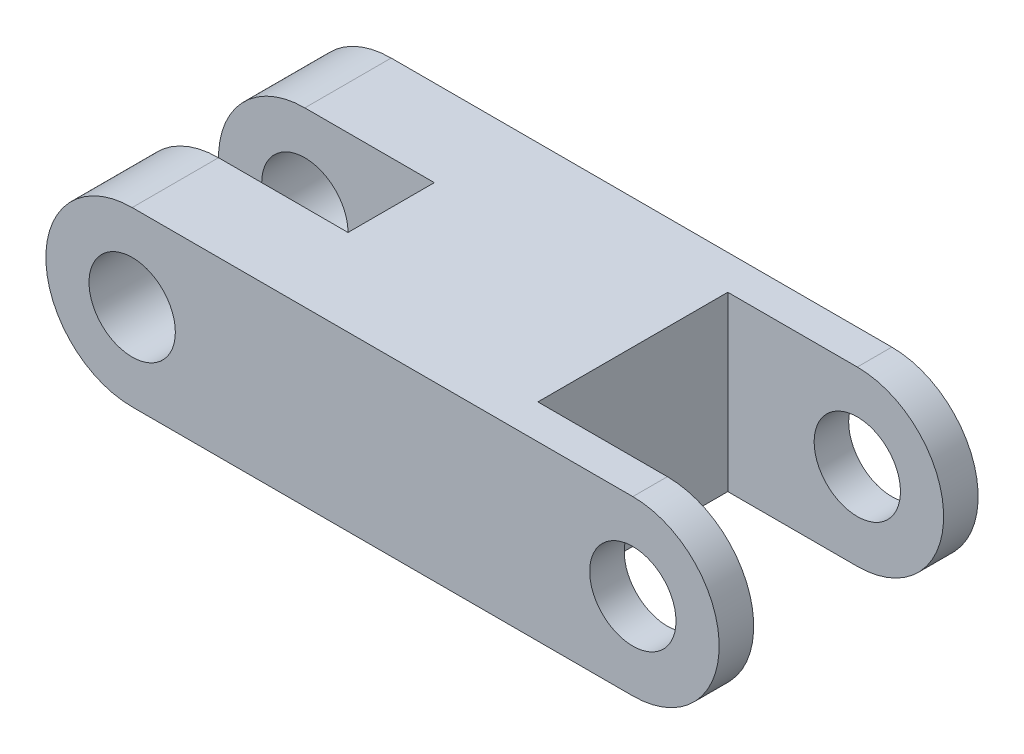
SolidWorks part; units mm, degrees
ref_plane "Front Plane" through (0, 0, 0) normal (0, 0, 1) x (1, 0, 0)
ref_plane "Top Plane" through (0, 0, 0) normal (0, 1, 0) x (1, 0, 0)
ref_plane "Right Plane" through (0, 0, 0) normal (1, 0, 0) x (0, 0, -1)
sketch "Sketch1" plane through (0, 0, 0) normal (0, 0, 1) x (1, 0, 0)
  line L0 (0, 0) -> (57.9939, 0) construction
  line L1 (0, 10) -> (57.9939, 10)
  line L2 (0, -10) -> (57.9939, -10)
  arc A0 (0, 10) -> (0, -10) centre (0, 0) ccw
  arc A1 (57.9939, -10) -> (57.9939, 10) centre (57.9939, 0) ccw
  circle A2 centre (0, 0) radius 5
  circle A3 centre (57.9939, 0) radius 5
  point P3 (28.9969, 0)
  point P12 (69.5171, 0)
  point P13 (45.3594, 0)
  point P14 (67.7353, 0)
  point P15 (50.081, 0)
  point P16 (61.8962, 0)
  point P17 (55.6919, 0)
  point P18 (0, 0)
  point P19 (57.9939, 0)
  dimension "D1" = 10
  dimension "D2" = 10
  dimension "D3" = 20
extrude "Boss-Extrude1" add sketch "Sketch1" along normal blind 30
sketch "Sketch2" plane through (0, 10, 0) normal (0, 1, 0) x (1, 0, 0)
  line L0 (-10, 0) -> (-10, -30) construction
  line L1 (15, -10) -> (-10, -10)
  line L2 (15, -10) -> (15, -20)
  line L3 (15, -20) -> (-10, -20)
  line L4 (-10, -10) -> (-10, -20)
  line L5 (67.9939, -30) -> (67.9939, 0) construction
  line L6 (0, -30) -> (0, 0) construction
  line L15 (42.9939, -26) -> (67.9939, -26)
  line L16 (42.9939, -26) -> (42.9939, -4)
  line L17 (42.9939, -4) -> (67.9939, -4)
  line L18 (67.9939, -26) -> (67.9939, -4)
  line L19 (57.9939, -30) -> (57.9939, 0) construction
  point P7 (-10, -15)
  point P10 (0, -15)
  point P15 (67.9939, -15)
  point P19 (57.9939, -15)
  dimension "D1" = 10
  dimension "D2" = 25
  dimension "D3" = 22
  dimension "D4" = 25
extrude "Cut-Extrude1" cut sketch "Sketch2" against normal through all
